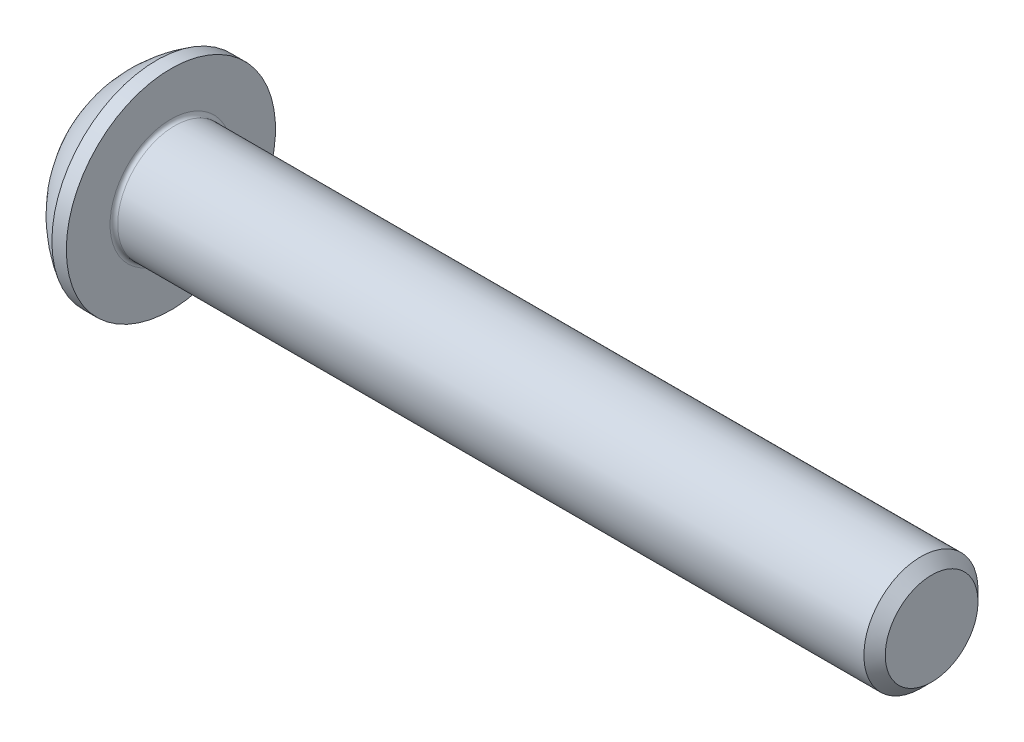
SolidWorks part; units mm, degrees
material "Plain Carbon Steel"
ref_plane "Front Plane" through (0, 0, 0) normal (0, 0, 1) x (1, 0, 0)
ref_plane "Top Plane" through (0, 0, 0) normal (0, 1, 0) x (1, 0, 0)
ref_plane "Right Plane" through (0, 0, 0) normal (1, 0, 0) x (0, 0, -1)
ref_plane "Plane1" through (0, 0, 0) normal (0, 0, -1) x (-1, 0, 0)
sketch "Sketch1" plane through (0, 0, 0) normal (0, 0, -1) x (-1, 0, 0)
  line L0 (-1.65, 2.75) -> (-1.65, 0)
  line L1 (-1.65, 0) -> (0, 0)
  line L2 (0, 0) -> (0, 1.425)
  line L3 (-1.27, 2.75) -> (-1.65, 2.75)
  line L4 (-1.65, 0) -> (0, 0) construction
  arc A0 (0, 1.425) -> (-1.27, 2.75) centre (-2.962, -0.1429) ccw
  dimension "D5" = 3.3514
  dimension "D1" = 2.75
  dimension "D2" = 1.65
  dimension "D3" = 1.425
  dimension "D4" = 0.38
revolve "Revolve1" add sketch "Sketch1" angle 360 about L4
sketch "Sketch2" plane through (0, 0, 0) normal (-1, 0, 0) x (0, 0, 1)
  line L7 (-1, 0.5774) -> (-1, -0.5774)
  line L8 (-1, -0.5774) -> (0, -1.1547)
  line L9 (0, -1.1547) -> (1, -0.5774)
  line L10 (1, -0.5774) -> (1, 0.5774)
  line L11 (1, 0.5774) -> (0, 1.1547)
  line L12 (0, 1.1547) -> (-1, 0.5774)
  circle A0 centre (0, 0) radius 1 construction
  dimension "D1" = 2
extrude "Cut-Extrude1" cut sketch "Sketch2" against normal blind 1.04
sketch "Sketch3" plane through (0, 0, 0) normal (0, 0, 1) x (1, 0, 0)
  line L0 (1.04, 1) -> (1.04, 0)
  line L1 (1.04, 0) -> (1.6174, 0)
  line L2 (1.6174, 0) -> (1.04, 1)
  line L3 (1.04, 0) -> (1.6174, 0) construction
revolve "Cut-Revolve1" cut sketch "Sketch3" angle 360 about L3
sketch "Sketch4" plane through (1.65, 0, 0) normal (1, 0, 0) x (0, 0, -1)
  circle A0 centre (0, 0) radius 1.5
extrude "Largo y Ancho rosca" add sketch "Sketch4" along normal blind 20
fillet "Fillet1" radius 0.1 1 edges at (1.65, 0, -1.5)
chamfer "Chamfer1" distance 0.2805 angle 45 1 edges at (21.65, 0, -1.5)
